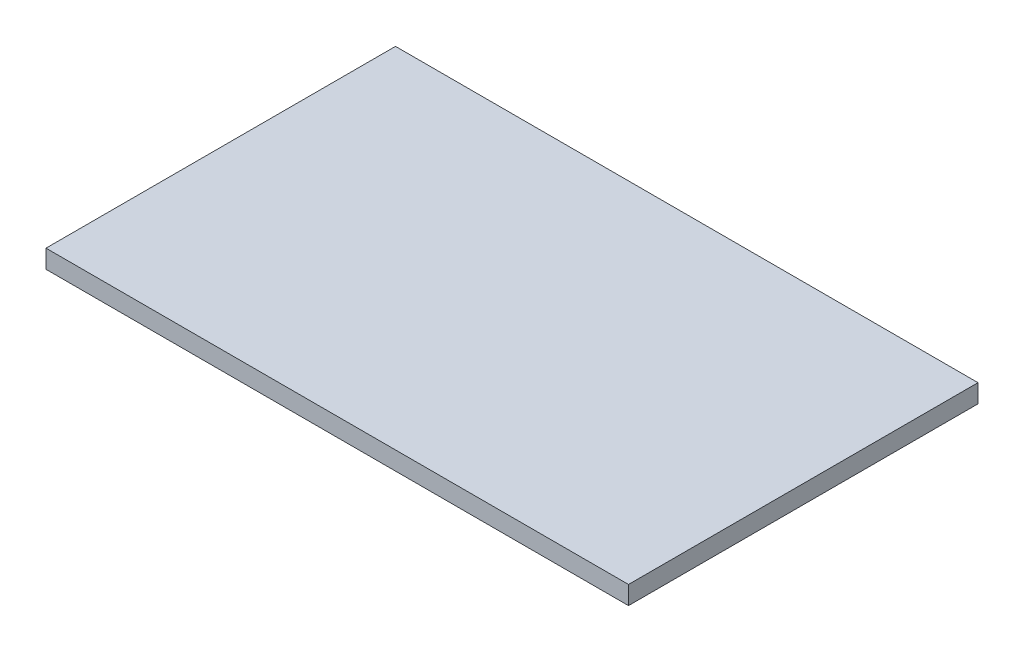
SolidWorks part; units mm, degrees
ref_plane "Front Plane" through (0, 0, 0) normal (0, 0, 1) x (1, 0, 0)
ref_plane "Top Plane" through (0, 0, 0) normal (0, 1, 0) x (1, 0, 0)
ref_plane "Right Plane" through (0, 0, 0) normal (1, 0, 0) x (0, 0, -1)
sketch "Sketch1" plane through (0, 0, 0) normal (0, 1, 0) x (1, 0, 0)
  line L1 (-25.4, -15.24) -> (25.4, -15.24)
  line L2 (-25.4, -15.24) -> (-25.4, 15.24)
  line L3 (-25.4, 15.24) -> (25.4, 15.24)
  line L4 (25.4, -15.24) -> (25.4, 15.24)
  line L5 (-25.4, -15.24) -> (25.4, 15.24) construction
  line L6 (-25.4, 15.24) -> (25.4, -15.24) construction
  point P0 (0, 0)
  dimension "D1" = 30.48
  dimension "D2" = 50.8
extrude "Boss-Extrude1" add sketch "Sketch1" along normal mid plane 1.6
